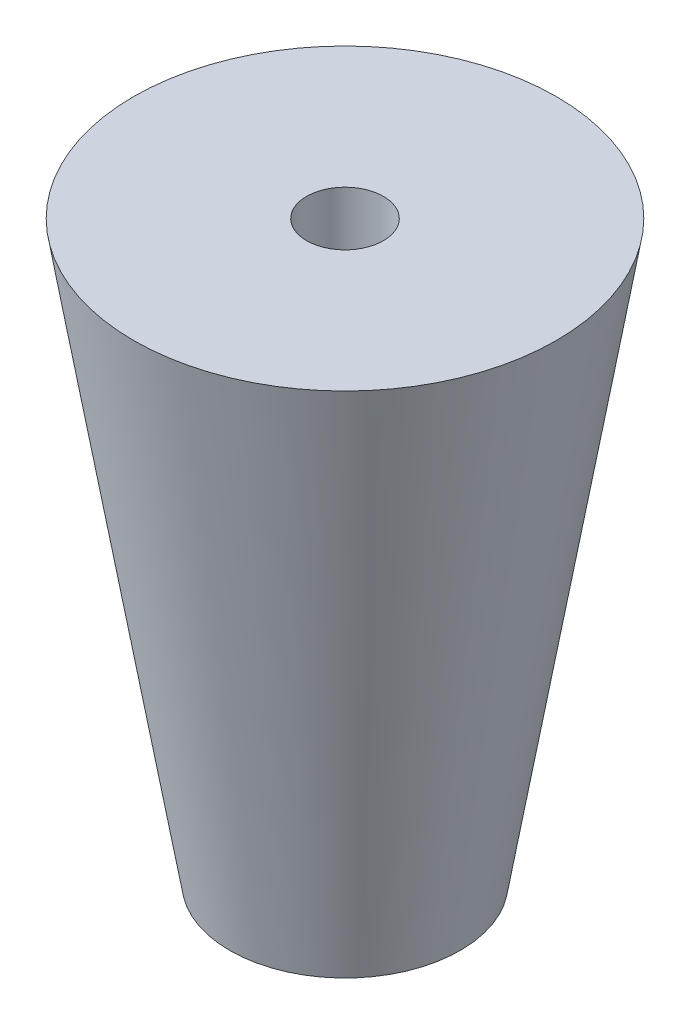
SolidWorks part; units mm, degrees
material "Silicon Rubber"
ref_plane "Front Plane" through (0, 0, 0) normal (0, 0, 1) x (1, 0, 0)
ref_plane "Top Plane" through (0, 0, 0) normal (0, 1, 0) x (1, 0, 0)
ref_plane "Right Plane" through (0, 0, 0) normal (1, 0, 0) x (0, 0, -1)
sketch "Sketch1" plane through (0, 0, 0) normal (1, 0, 0) x (0, 0, -1)
  line L1 (1, 15) -> (5.5, 15)
  line L2 (5.5, 15) -> (3, 0)
  line L3 (3, 0) -> (1, 0)
  line L4 (0, 0) -> (0, -19.7923) construction
  line L5 (1, 15) -> (1, 0)
  dimension "D3" = 4.5
  dimension "D4" = 2
revolve "Revolve1" add sketch "Sketch1" angle 360 about L4
